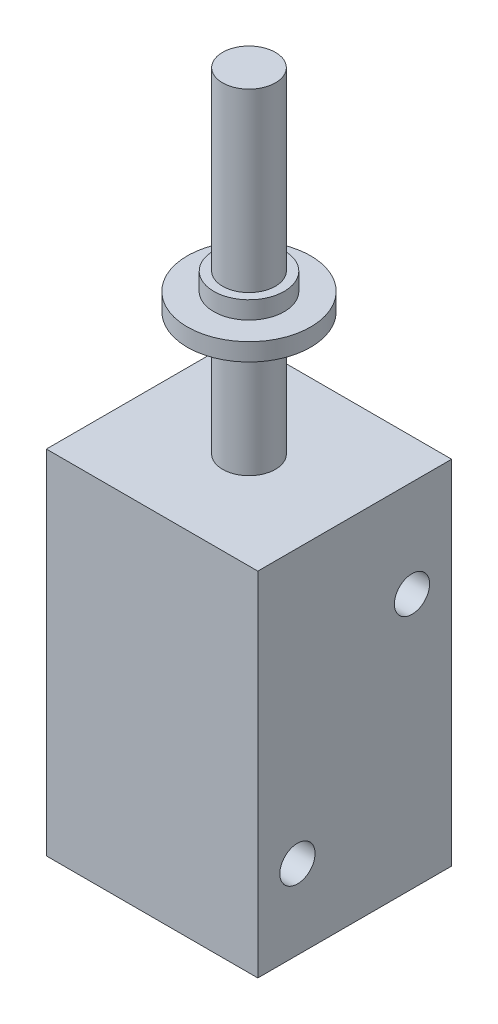
SolidWorks part; units mm, degrees
ref_plane "Front Plane" through (0, 0, 0) normal (0, 0, 1) x (1, 0, 0)
ref_plane "Top Plane" through (0, 0, 0) normal (0, 1, 0) x (1, 0, 0)
ref_plane "Right Plane" through (0, 0, 0) normal (1, 0, 0) x (0, 0, -1)
sketch "Sketch1" plane through (0, 0, 0) normal (0, 1, 0) x (1, 0, 0)
  line L1 (0, 0) -> (12, 0)
  line L2 (0, 0) -> (0, 11)
  line L3 (0, 11) -> (12, 11)
  line L4 (12, 0) -> (12, 11)
  dimension "D1" = 12
  dimension "D2" = 11
extrude "Boss-Extrude1" add sketch "Sketch1" along normal blind 20
sketch "Sketch2" plane through (0, 20, 0) normal (0, 1, 0) x (1, 0, 0)
  line L0 (-0.6033, 5.5) -> (12.6033, 5.5) construction
  line L1 (6, -0.6264) -> (6, 11.6264) construction
  line L2 (12, 11) -> (0, 11) construction
  line L3 (0, 11) -> (0, 0) construction
  circle A0 centre (6, 5.5) radius 1.5
  point P6 (6, 11)
  point P9 (0, 5.5)
  dimension "D1" = 3
extrude "Boss-Extrude2" add sketch "Sketch2" along normal blind 19
ref_plane "Plane1" through (0, 27, 0) normal (0, 1, 0) x (1, 0, 0)
sketch "Sketch3" plane through (0, 27, 0) normal (0, 1, 0) x (1, 0, 0)
  circle A0 centre (6, 5.5) radius 3.5
  dimension "D1" = 7
extrude "Boss-Extrude3" add sketch "Sketch3" along normal blind 1
sketch "Sketch4" plane through (0, 28, 0) normal (0, 1, 0) x (1, 0, 0)
  circle A0 centre (6, 5.5) radius 2
  dimension "D1" = 4
extrude "Boss-Extrude4" add sketch "Sketch4" along normal blind 1
sketch "Sketch5" plane through (12, 0, 0) normal (1, 0, 0) x (0, 0, -1)
  line L0 (11, 20) -> (11, 0) construction
  line L1 (0, 20) -> (0, 0) construction
  line L2 (0, 0) -> (11, 0) construction
  circle A0 centre (2.25, 4.5) radius 1
  circle A1 centre (8.75, 14.5) radius 1
  dimension "D3" = 2
  dimension "D4" = 2
  dimension "D1" = 2.25
  dimension "D2" = 2.25
  dimension "D5" = 4.5
  dimension "D6" = 10
extrude "Cut-Extrude1" cut sketch "Sketch5" against normal up to surface (12 mm away) up to face at (0, 10, -5.5)
